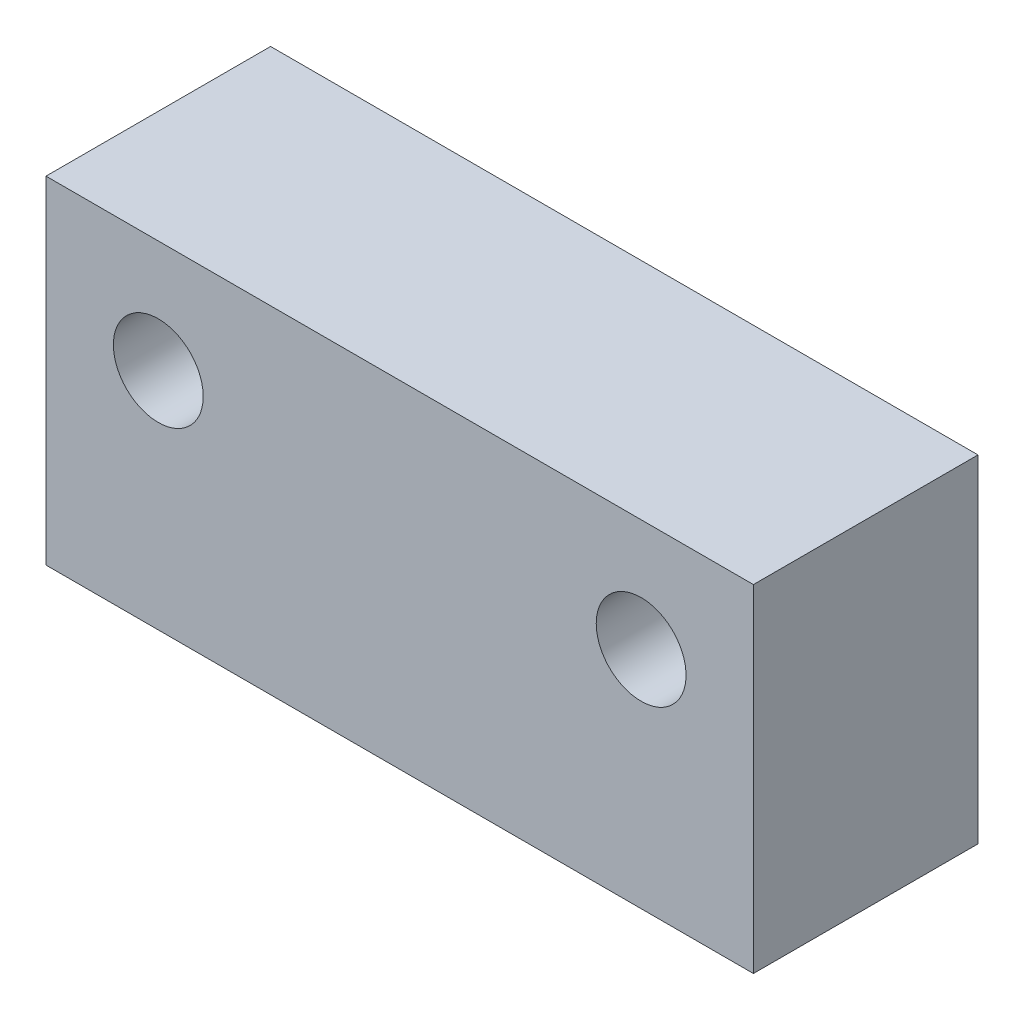
SolidWorks part; units mm, degrees
ref_plane "Front Plane" through (0, 0, 0) normal (0, 0, 1) x (1, 0, 0)
ref_plane "Top Plane" through (0, 0, 0) normal (0, 1, 0) x (1, 0, 0)
ref_plane "Right Plane" through (0, 0, 0) normal (1, 0, 0) x (0, 0, -1)
sketch "Sketch1" plane through (0, 0, 0) normal (0, 0, 1) x (1, 0, 0)
  line L0 (31.5, 30) -> (31.5, 0) construction
  line L1 (0, 0) -> (63, 0)
  line L2 (0, 0) -> (0, 30)
  line L3 (0, 30) -> (63, 30)
  line L4 (63, 0) -> (63, 30)
  circle A0 centre (10, 20) radius 4
  circle A2 centre (53, 20) radius 4
  dimension "D1" = 8
  dimension "D2" = 21.5
  dimension "D3" = 10
  dimension "D4" = 10
  dimension "D5" = 20
extrude "Boss-Extrude1" add sketch "Sketch1" along normal blind 20
sketch "Sketch2" [suppressed] plane through (0, 0, 0) normal (0, 0, -1) x (-1, 0, 0)
  line L0 (-63, 30) -> (0, 30) construction
  line L1 (-21.5, 30) -> (-41.5, 30)
  line L3 (-21.5, 8) -> (-41.5, 8)
  line L4 (-41.5, 30) -> (-41.5, 8)
  line L6 (-31.5, 30) -> (-31.5, 8) construction
  line L7 (-21.5, 30) -> (-21.5, 8)
  point P7 (-31.5, 30)
  dimension "D1" = 10
  dimension "D2" = 24
extrude "Cut-Extrude1" [suppressed] cut sketch "Sketch2" against normal blind 26
sketch "Sketch3" [suppressed] plane through (0, 0, 0) normal (0, 0, -1) x (-1, 0, 0)
  line L0 (-41.5, 30) -> (-41.5, 12) construction
  line L1 (-41.5, 30) -> (-57.5, 30)
  line L2 (-41.5, 30) -> (-41.5, 0)
  line L3 (-41.5, 0) -> (-57.5, 0)
  line L4 (-57.5, 30) -> (-57.5, 0)
  line L5 (0, 0) -> (-63, 0) construction
  line L6 (-63, 30) -> (-41.5, 30) construction
  dimension "D2" = 16
extrude "Boss-Extrude2" [suppressed] add sketch "Sketch3" along normal blind 25
sketch "Sketch4" [suppressed] plane through (41.5, 0, 0) normal (-1, 0, 0) x (0, 0, 1)
  line L0 (-25, 0) -> (0, 0) construction
  line L1 (-25, 0) -> (-25, 30) construction
  line L2 (-20, 23.65) -> (-10, 23.65)
  line L3 (-20, 18.65) -> (-10, 18.65)
  arc A0 (-20, 23.65) -> (-20, 18.65) centre (-20, 21.15) ccw
  arc A1 (-10, 18.65) -> (-10, 23.65) centre (-10, 21.15) ccw
  dimension "D2" = 5
  dimension "D4" = 5
  dimension "D5" = 10
  dimension "D1" = 21.15
  dimension "D3" = 5
extrude "Cut-Extrude2" [suppressed] cut sketch "Sketch4" against normal through all
